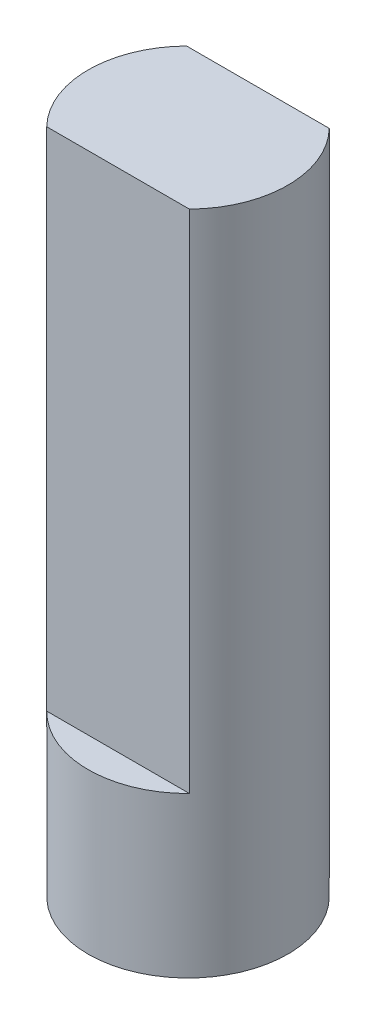
SolidWorks part; units mm, degrees
material "不锈钢 (铁素体)"
ref_plane "前视基准面" through (0, 0, 0) normal (0, 0, 1) x (1, 0, 0)
ref_plane "上视基准面" through (0, 0, 0) normal (0, 1, 0) x (1, 0, 0)
ref_plane "右视基准面" through (0, 0, 0) normal (1, 0, 0) x (0, 0, -1)
sketch "草图1" plane through (0, 0, 0) normal (0, 1, 0) x (1, 0, 0)
  circle A0 centre (0, 0) radius 3
  dimension "D1" = 6
extrude "凸台-拉伸1" add sketch "草图1" along normal blind 20
sketch "草图2" plane through (0, 20, 0) normal (0, 1, 0) x (1, 0, 0)
  line L0 (-2.1424, 2.1) -> (2.1424, 2.1)
  line L1 (-2.1424, -2.1) -> (2.1424, -2.1)
  arc A0 (-2.1424, -2.1) -> (2.1424, -2.1) centre (0, 0) ccw
  arc A1 (2.1424, 2.1) -> (-2.1424, 2.1) centre (0, 0) ccw
  dimension "D1" = 6
  dimension "D2" = 4.2
extrude "切除-拉伸2" cut sketch "草图2" against normal blind 15.2
